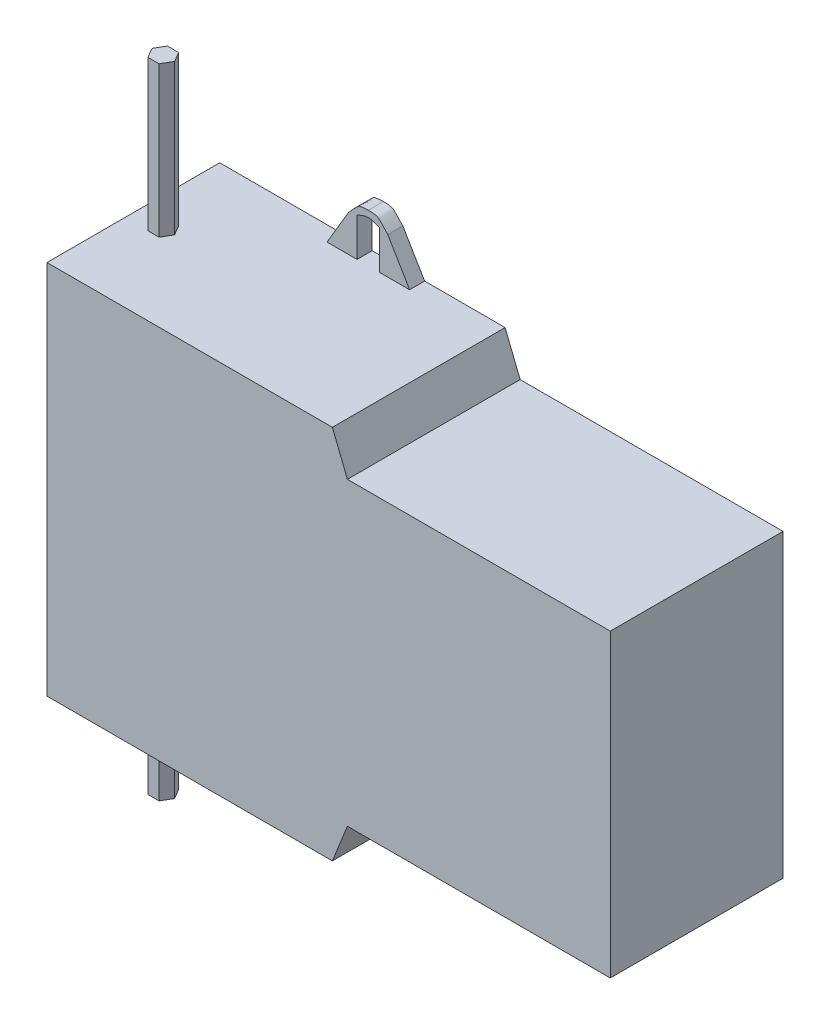
SolidWorks part; units mm, degrees
ref_plane "Front Plane" through (0, 0, 0) normal (0, 0, 1) x (1, 0, 0)
ref_plane "Top Plane" through (0, 0, 0) normal (0, 1, 0) x (1, 0, 0)
ref_plane "Right Plane" through (0, 0, 0) normal (1, 0, 0) x (0, 0, -1)
sketch "Sketch1" plane through (0, 0, 0) normal (0, 0, 1) x (1, 0, 0)
  line L0 (38, 50) -> (40, 45)
  line L1 (40, 5) -> (75, 5)
  line L2 (0, 0) -> (0, 50)
  line L3 (0, 50) -> (38, 50)
  line L4 (0, 25) -> (150, 25) construction
  line L5 (40, 45) -> (75, 45)
  line L6 (0, 0) -> (38, 0)
  line L7 (38, 0) -> (40, 5)
  line L8 (75, 45) -> (75, 5)
  point P6 (75, 25)
  point P9 (75, 25)
  dimension "D3" = 75
  dimension "D4" = 38
  dimension "D5" = 35
extrude "Boss-Extrude1" add sketch "Sketch1" along normal blind 23
sketch "Sketch2" plane through (0, 0, 0) normal (0, 0, -1) x (-1, 0, 0)
  line L0 (-27.2831, 50) -> (-24.3764, 54.9155)
  line L1 (-38, 50) -> (0, 50) construction
  line L2 (-19.1897, 54.9155) -> (-16.2831, 50)
  line L3 (-16.2831, 50) -> (-27.2831, 50)
  line L4 (-21.7831, 50) -> (-21.7831, 55.1165) construction
  line L5 (-29.9077, 56.3) -> (-21.7831, 56.3) construction
  line L6 (-20.0084, 56.3) -> (-7.8131, 56.3) construction
  line L7 (-21.7831, 59.3012) -> (-21.7831, 65.58) construction
  line L8 (-21.7831, 55.5719) -> (-21.7831, 56.4169) construction
  line L9 (-23.2831, 50) -> (-20.2831, 50)
  line L10 (-23.2831, 50) -> (-23.2831, 55.1165)
  line L12 (-20.2831, 50) -> (-20.2831, 55.1165)
  spline S0 degree 3 poles (-24.3764, 54.9155) (-23.9195, 55.4266) (-23.0838, 56.3187) (-22.7702, 56.3298) (-22.1359, 56.4399) (-21.7831, 56.4169) knots 0 0 0 0 0.318153 0.553621 0.816427 0.816427 0.816427 0.816427
  spline S1 degree 3 poles (-19.1897, 54.9155) (-19.6466, 55.4266) (-20.4823, 56.3187) (-20.796, 56.3298) (-21.4302, 56.4399) (-21.7831, 56.4169) knots 0 0 0 0 0.318153 0.553621 0.816427 0.816427 0.816427 0.816427
  spline S2 degree 3 poles (-23.2831, 55.1165) (-22.7831, 55.3442) (-21.7831, 55.7996) (-20.7831, 55.3442) (-20.2831, 55.1165) knots 0 0 0 0 0.5 1 1 1 1
  line M4 (0, 50) -> (-38, 50)
  dimension "D1" = 11
  dimension "D2" = 6.3
  dimension "D3" = 1.5
  dimension "D4" = 3
extrude "Boss-Extrude2" add sketch "Sketch2" against normal blind 2 contours L10 S2 L12 L2 S1 S0 L0 M4
ref_plane "Plane1" through (0, 25, 0) normal (0, 1, 0) x (-1, 0, 0)
mirror "Mirror1" about plane through (0, 25, 0) normal (0, 1, 0) of "Boss-Extrude2"
sketch "Sketch3" plane through (0, 0, 0) normal (0, -1, 0) x (1, 0, 0)
  line L0 (0, 23) -> (0, 0) construction
  line L1 (5.3022, 11.32) -> (4.5517, 12.62)
  line L2 (4.5517, 12.62) -> (3.0506, 12.62)
  line L3 (3.0506, 12.62) -> (2.3, 11.32)
  line L4 (2.3, 11.32) -> (3.0506, 10.02)
  line L5 (3.0506, 10.02) -> (4.5517, 10.02)
  line L6 (4.5517, 10.02) -> (5.3022, 11.32)
  line L7 (16.2831, 0) -> (0, 0) construction
  circle A0 centre (3.8011, 11.32) radius 1.3 construction
  dimension "D1" = 2.6
  dimension "D2" = 2.3
  dimension "D3" = 12.62
extrude "Boss-Extrude3" add sketch "Sketch3" along normal blind 15 and the other way blind 70
